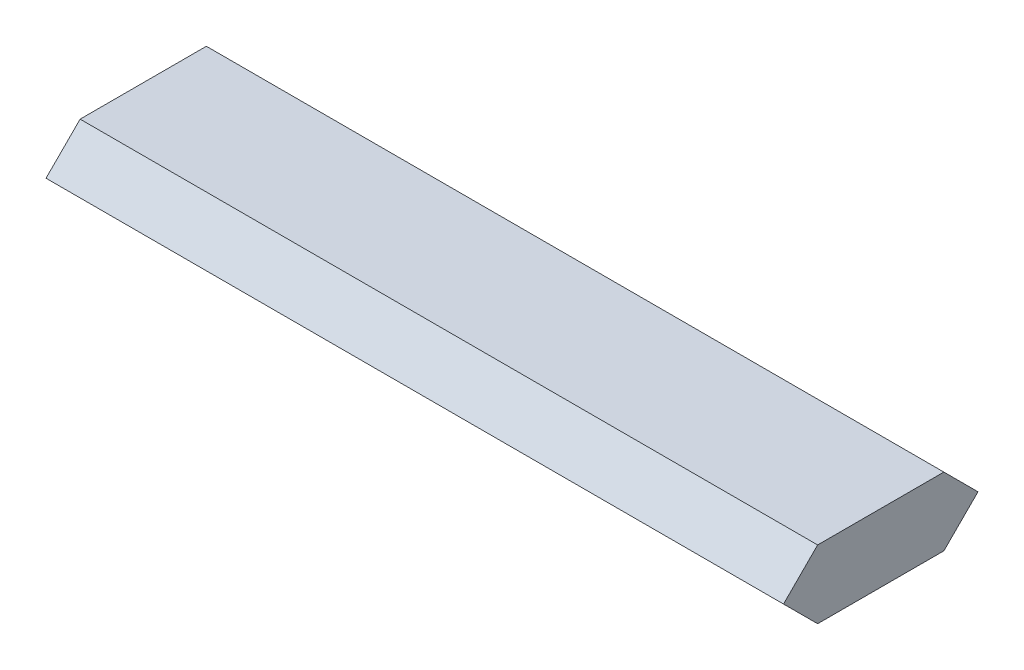
SolidWorks part; units mm, degrees
ref_plane "Front Plane" through (0, 0, 0) normal (0, 0, 1) x (1, 0, 0)
ref_plane "Top Plane" through (0, 0, 0) normal (0, 1, 0) x (1, 0, 0)
ref_plane "Right Plane" through (0, 0, 0) normal (1, 0, 0) x (0, 0, -1)
sketch "Sketch2" plane through (0, 0, 0) normal (1, 0, 0) x (0, 0, -1)
  line L0 (-2.7173, 2.9378) -> (-4.1862, 1.4689)
  line L1 (-2.7173, 0) -> (-4.1862, 1.4689)
  line L2 (-2.7173, 0) -> (2.7173, 0)
  line L3 (2.7173, 2.9378) -> (4.1862, 1.4689)
  line L4 (2.7173, 0) -> (4.1862, 1.4689)
  line L5 (-2.7173, 2.9378) -> (2.7173, 2.9378)
  point P4 (0, 0)
  dimension "D1" = 5.4345
  dimension "D2" = 5.4345
extrude "Boss-Extrude1" add sketch "Sketch2" along normal mid plane 31.75
